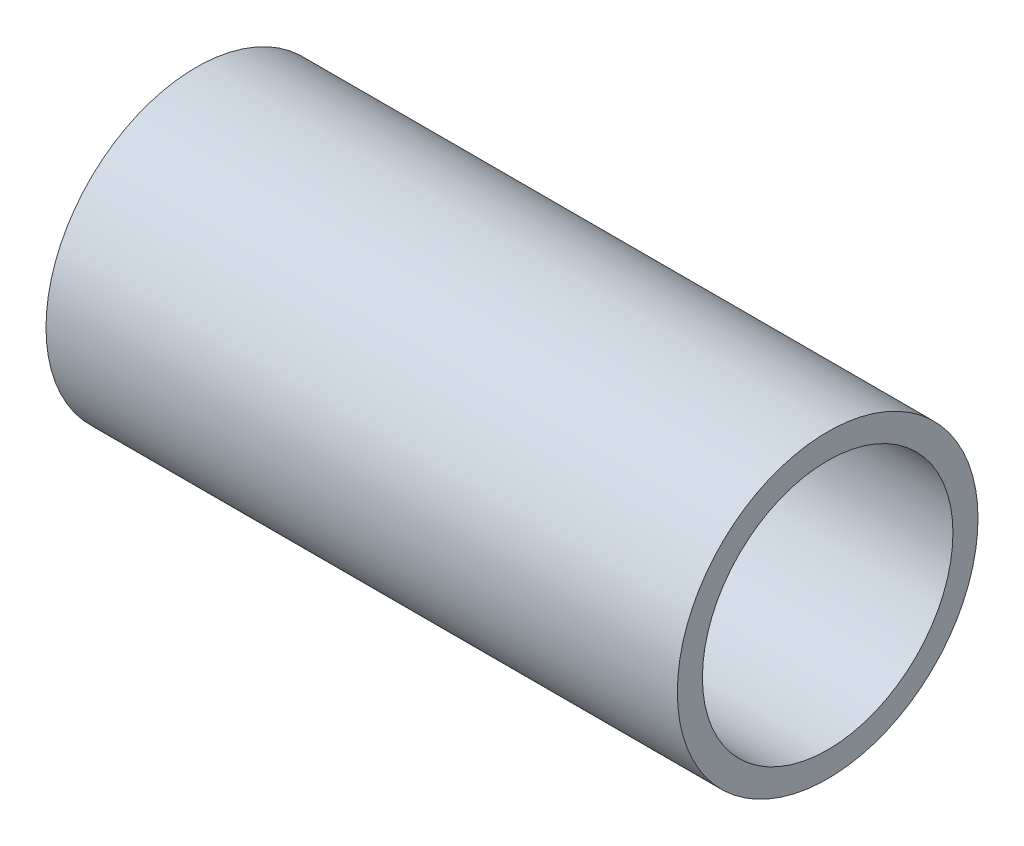
SolidWorks part; units mm, degrees
ref_plane "Front Plane" through (0, 0, 0) normal (0, 0, 1) x (1, 0, 0)
ref_plane "Top Plane" through (0, 0, 0) normal (0, 1, 0) x (1, 0, 0)
ref_plane "Right Plane" through (0, 0, 0) normal (1, 0, 0) x (0, 0, -1)
sketch "Sketch1" plane through (0, 0, 0) normal (1, 0, 0) x (0, 0, -1)
  circle A0 centre (0, 0) radius 12.5
  circle A1 centre (0, 0) radius 15
  dimension "D1" = 30
  dimension "D2" = 25
extrude "Boss-Extrude1" add sketch "Sketch1" along normal blind 63
